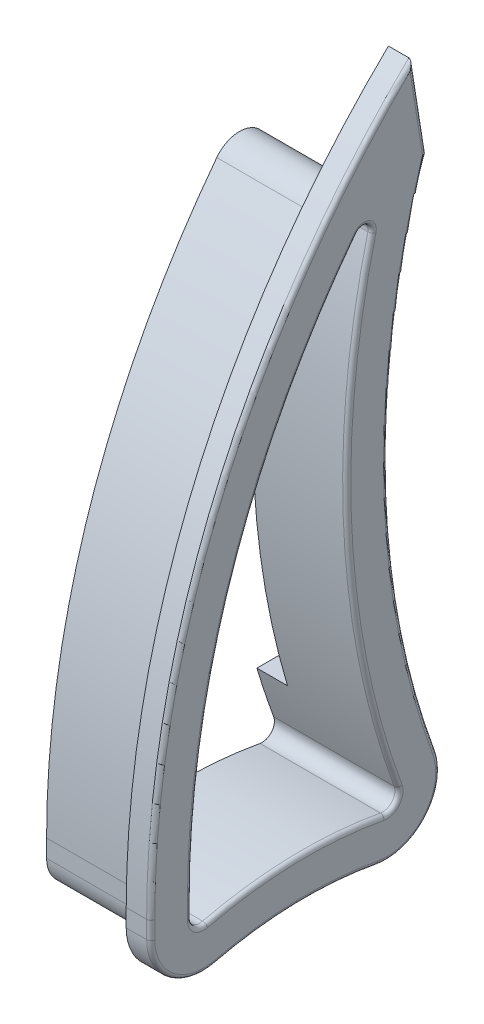
SolidWorks part; units mm, degrees
material "ABS"
ref_plane "Front Plane" through (0, 0, 0) normal (0, 0, 1) x (1, 0, 0)
ref_plane "Top Plane" through (0, 0, 0) normal (0, 1, 0) x (1, 0, 0)
ref_plane "Right Plane" through (0, 0, 0) normal (1, 0, 0) x (0, 0, -1)
sketch "Sketch1" plane through (0, 0, 0) normal (1, 0, 0) x (0, 0, -1)
  line L0 (-8.89, 10.8516) -> (-8.89, 9.7564)
  line L1 (0, 0) -> (0, 8.4759) construction
  arc A0 (3.2842, 44.1965) -> (-8.89, 10.8516) centre (42.8625, 10.8516) ccw
  arc A1 (5.4713, 43.0113) -> (3.2842, 44.1965) centre (4.2555, 43.3782) ccw
  arc A2 (5.4713, 43.0113) -> (6.4278, 10.7568) centre (54.1734, 28.3141) ccw
  arc A3 (4.1515, 8.0574) -> (6.4278, 10.7568) centre (4.5206, 10.0555) ccw
  arc A4 (4.1515, 8.0574) -> (-6.3843, 7.7804) centre (-0.4634, -16.9199) ccw
  arc A5 (-8.89, 9.7564) -> (-6.3843, 7.7804) centre (-6.858, 9.7564) ccw
sketch "Sketch2" plane through (0, 0, 0) normal (1, 0, 0) x (0, 0, -1)
  line L0 (-10.16, 10.8516) -> (-10.16, 9.7564)
  arc A12 (6.6872, 42.6444) -> (2.313, 45.0148) centre (4.2555, 43.3782) ccw
  arc A13 (-10.16, 9.7564) -> (-6.0883, 6.5453) centre (-6.858, 9.7564) ccw
  arc A14 (3.9207, 6.8085) -> (7.6198, 11.1952) centre (4.5206, 10.0555) ccw
  arc A15 (3.9207, 6.8085) -> (-6.0883, 6.5453) centre (-0.4634, -16.9199) ccw
  arc A16 (6.6872, 42.6444) -> (7.6198, 11.1952) centre (54.1734, 28.3141) ccw
  arc A17 (2.313, 45.0148) -> (-10.16, 10.8516) centre (42.8625, 10.8516) ccw
  arc A18 (6.6872, 42.6444) -> (2.313, 45.0148) centre (4.2555, 43.3782) ccw
  arc A19 (-10.16, 9.7564) -> (-6.0883, 6.5453) centre (-6.858, 9.7564) ccw
  arc A20 (3.9207, 6.8085) -> (7.6198, 11.1952) centre (4.5206, 10.0555) ccw
  arc A21 (3.9207, 6.8085) -> (-6.0883, 6.5453) centre (-0.4634, -16.9199) ccw
  arc A22 (6.6872, 42.6444) -> (7.6198, 11.1952) centre (54.1734, 28.3141) ccw
  arc A23 (2.313, 45.0148) -> (-10.16, 10.8516) centre (42.8625, 10.8516) ccw
  dimension "D1" = 1.27
extrude "Boss-Extrude1" add sketch "Sketch2" along normal blind 1.524
sketch "Sketch3" plane through (1.524, 0, 0) normal (1, 0, 0) x (0, 0, -1)
  line L2 (-7.62, 10.8516) -> (-7.62, 9.7564)
  line L3 (-7.62, 10.8516) -> (-7.62, 9.7564)
  arc A12 (4.2555, 43.3782) -> (5.2358, 10.3185) centre (54.1734, 28.3141) ccw
  arc A14 (4.2555, 43.3782) -> (-7.62, 10.8516) centre (42.8625, 10.8516) ccw
  arc A15 (-7.62, 9.7564) -> (-6.6804, 9.0154) centre (-6.858, 9.7564) ccw
  arc A16 (4.3822, 9.3062) -> (-6.6804, 9.0154) centre (-0.4634, -16.9199) ccw
  arc A17 (4.3822, 9.3062) -> (5.2358, 10.3185) centre (4.5206, 10.0555) ccw
  arc A18 (4.2555, 43.3782) -> (5.2358, 10.3185) centre (54.1734, 28.3141) ccw
  arc A20 (4.2555, 43.3782) -> (-7.62, 10.8516) centre (42.8625, 10.8516) ccw
  arc A21 (-7.62, 9.7564) -> (-6.6804, 9.0154) centre (-6.858, 9.7564) ccw
  arc A22 (4.3822, 9.3062) -> (-6.6804, 9.0154) centre (-0.4634, -16.9199) ccw
  arc A23 (4.3822, 9.3062) -> (5.2358, 10.3185) centre (4.5206, 10.0555) ccw
  dimension "D1" = 2.54
sketch "Sketch5" plane through (1.524, 0, 0) normal (1, 0, 0) x (0, 0, -1)
  line L0 (7.0091, 43.6708) -> (6.1482, 49.1066)
  line L1 (7.0091, 43.6708) -> (1.2178, 43.6708) construction
  line L2 (1.2178, 43.6708) -> (6.5347, 42.1289)
  arc A0 (6.6872, 42.6444) -> (7.6198, 11.1952) centre (54.1734, 28.3141) ccw construction
  arc A1 (7.0091, 43.6708) -> (6.5347, 42.1289) centre (54.1734, 28.3141) ccw
  arc A2 (2.313, 45.0148) -> (-10.16, 10.8516) centre (42.8625, 10.8516) ccw construction
  arc A3 (6.1482, 49.1066) -> (1.2178, 43.6708) centre (42.8625, 10.8516) ccw
  dimension "D1" = 81
extrude "Kes-Ekstrüzyon1" cut sketch "Sketch3" against normal blind 2.54 contours A20 L3 A21 A22 A23 A18
fillet "Radyus1" radius 0.508 1 edges at (0.762, 43.3782, -4.2555)
sketch "Çizim3" plane through (0, 0, 0) normal (-1, 0, 0) x (0, 0, 1)
  line L1 (7.62, 10.8516) -> (7.62, 9.7564) construction
  line L2 (8.89, 9.7564) -> (8.89, 10.8516)
  line L3 (8.89, 9.7564) -> (8.89, 10.8516)
  line L4 (7.62, 10.8516) -> (7.62, 9.7564)
  arc A6 (6.6804, 9.0154) -> (-4.3822, 9.3062) centre (0.4634, -16.9199) ccw construction
  arc A7 (-5.2358, 10.3185) -> (-4.3822, 9.3062) centre (-4.5206, 10.0555) ccw construction
  arc A8 (-2.7049, 41.4432) -> (-3.6017, 41.0117) centre (-3.109, 41.1354) ccw construction
  arc A9 (-5.2358, 10.3185) -> (-3.6017, 41.0117) centre (-54.1734, 28.3141) ccw construction
  arc A10 (7.62, 10.8516) -> (-2.7049, 41.4432) centre (-42.8625, 10.8516) ccw construction
  arc A11 (6.6804, 9.0154) -> (7.62, 9.7564) centre (6.858, 9.7564) ccw construction
  arc A12 (-1.6946, 42.2128) -> (-4.8335, 40.7024) centre (-3.109, 41.1354) ccw
  arc A13 (-6.4278, 10.7568) -> (-4.8335, 40.7024) centre (-54.1734, 28.3141) ccw
  arc A14 (-6.4278, 10.7568) -> (-4.1515, 8.0574) centre (-4.5206, 10.0555) ccw
  arc A15 (6.3843, 7.7804) -> (-4.1515, 8.0574) centre (0.4634, -16.9199) ccw
  arc A16 (6.3843, 7.7804) -> (8.89, 9.7564) centre (6.858, 9.7564) ccw
  arc A17 (8.89, 10.8516) -> (-1.6946, 42.2128) centre (-42.8625, 10.8516) ccw
  arc A18 (-1.6946, 42.2128) -> (-4.8335, 40.7024) centre (-3.109, 41.1354) ccw
  arc A19 (-6.4278, 10.7568) -> (-4.8335, 40.7024) centre (-54.1734, 28.3141) ccw
  arc A20 (-6.4278, 10.7568) -> (-4.1515, 8.0574) centre (-4.5206, 10.0555) ccw
  arc A21 (6.3843, 7.7804) -> (-4.1515, 8.0574) centre (0.4634, -16.9199) ccw
  arc A22 (6.3843, 7.7804) -> (8.89, 9.7564) centre (6.858, 9.7564) ccw
  arc A23 (8.89, 10.8516) -> (-1.6946, 42.2128) centre (-42.8625, 10.8516) ccw
  arc A24 (-2.7049, 41.4432) -> (-3.6017, 41.0117) centre (-3.109, 41.1354) ccw
  arc A25 (-5.2358, 10.3185) -> (-3.6017, 41.0117) centre (-54.1734, 28.3141) ccw
  arc A26 (-5.2358, 10.3185) -> (-4.3822, 9.3062) centre (-4.5206, 10.0555) ccw
  arc A27 (7.62, 10.8516) -> (-2.7049, 41.4432) centre (-42.8625, 10.8516) ccw
  arc A28 (6.6804, 9.0154) -> (7.62, 9.7564) centre (6.858, 9.7564) ccw
  arc A29 (6.6804, 9.0154) -> (-4.3822, 9.3062) centre (0.4634, -16.9199) ccw
  dimension "D1" = 1.27
extrude "Yükseklik-Ekstrüzyon1" add sketch "Çizim3" along normal blind 6.223
extrude "Yükseklik-Ekstrüzyon2" add sketch "Sketch5" against normal up to surface (1.524 mm away) contours A3 L2 A1 L0 up to face at (0, 19.1554, 1.4286)
sketch "Çizim5" plane through (0, 0, 0) normal (0, 0, 1) x (1, 0, 0)
  line L1 (-6.223, 13.462) -> (-4.318, 13.462)
  line L2 (-6.223, 13.462) -> (-6.223, 37.338)
  line L3 (-6.223, 37.338) -> (-4.318, 37.338)
  line L4 (-4.318, 13.462) -> (-4.318, 37.338)
  dimension "D1" = 1.905
extrude "Kes-Ekstrüzyon2" cut sketch "Çizim5" against normal blind 9.779 contours L2 L3 L4 L1
fillet "Radyus2" radius 0.254 14 edges at (1.524, 10.304, 7.62) (1.524, 9.1581, 7.3299) (1.524, 9.7409, 1.1643) (1.524, 9.5643, -5.1032) (1.524, 25.542, -2.1057) (1.524, 41.5932, -3.3293) (1.524, 26.9951, 4.9692) (1.524, 7.9269, -7.045) (1.524, 7.2018, 1.0976) (1.524, 7.1636, 8.9027) (1.524, 10.304, 10.16) (1.524, 31.6446, 5.9129) (1.524, 46.3887, -6.5786) (1.524, 27.3816, -4.5808)
